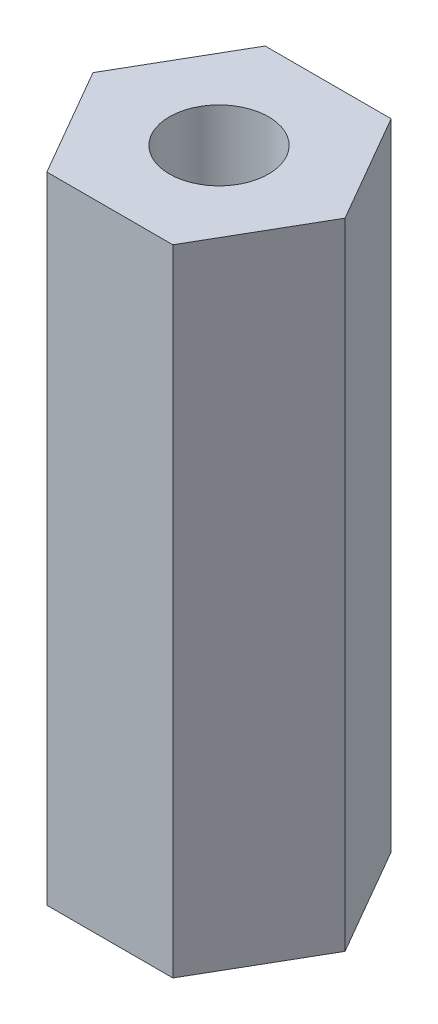
SolidWorks part; units mm, degrees
ref_plane "Front" through (0, 0, 0) normal (0, 0, 1) x (1, 0, 0)
ref_plane "Top" through (0, 0, 0) normal (0, 1, 0) x (1, 0, 0)
ref_plane "Right" through (0, 0, 0) normal (1, 0, 0) x (0, 0, -1)
sketch "Sketch1" plane through (0, 0, 0) normal (0, 1, 0) x (1, 0, 0)
  line L1 (3.1754, 0) -> (1.5877, 2.75)
  line L2 (1.5877, 2.75) -> (-1.5877, 2.75)
  line L3 (-1.5877, 2.75) -> (-3.1754, 0)
  line L4 (-3.1754, 0) -> (-1.5877, -2.75)
  line L5 (-1.5877, -2.75) -> (1.5877, -2.75)
  line L6 (1.5877, -2.75) -> (3.1754, 0)
  circle A0 centre (0, 0) radius 1.25
  circle A1 centre (0, 0) radius 2.75 construction
extrude "Boss-Extrude1" add sketch "Sketch1" along normal blind 16
